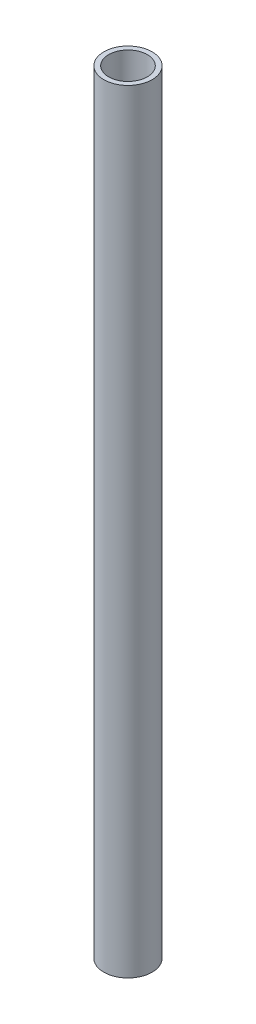
SolidWorks part; units mm, degrees
ref_plane "Front Plane" through (0, 0, 0) normal (0, 0, 1) x (1, 0, 0)
ref_plane "Top Plane" through (0, 0, 0) normal (0, 1, 0) x (1, 0, 0)
ref_plane "Right Plane" through (0, 0, 0) normal (1, 0, 0) x (0, 0, -1)
sketch "Sketch1" plane through (0, 0, 0) normal (0, 1, 0) x (1, 0, 0)
  circle A0 centre (0, 0) radius 2
  circle A1 centre (0, 0) radius 2.5
  dimension "D1" = 5
  dimension "D2" = 4
extrude "Boss-Extrude2" add sketch "Sketch1" along normal blind 80
